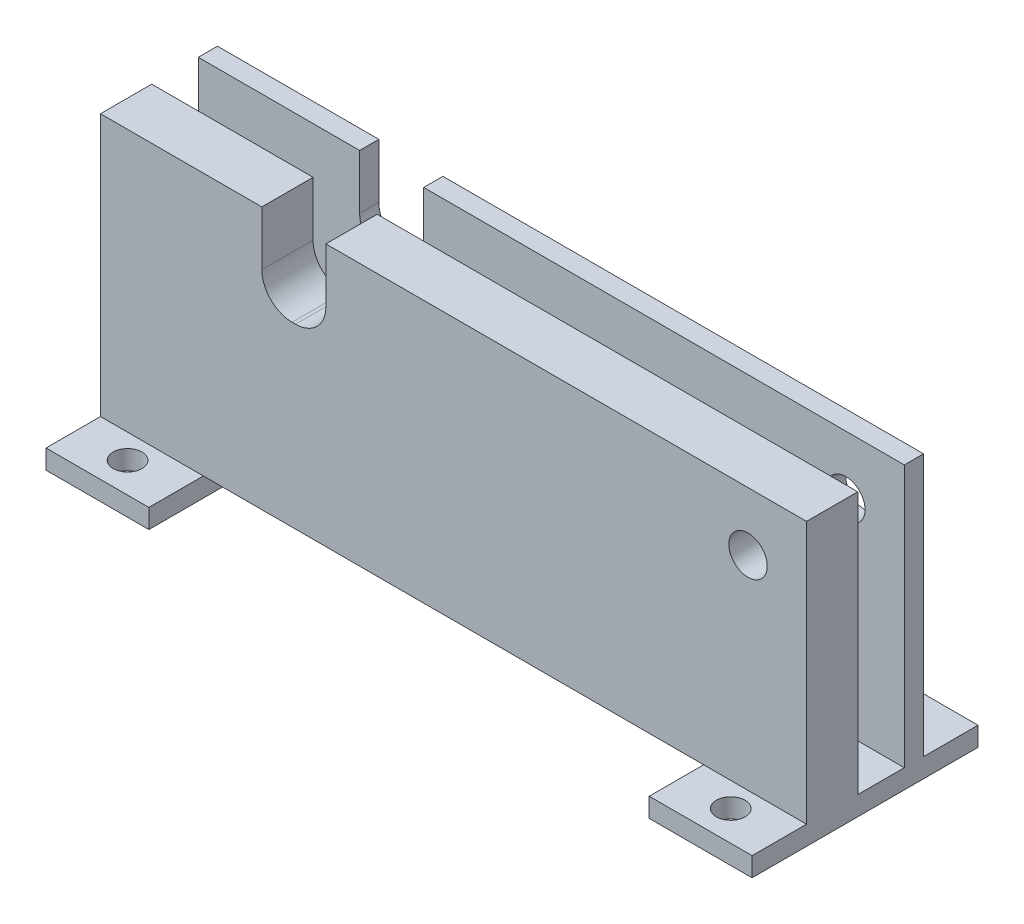
SolidWorks part; units mm, degrees
ref_plane "Alzado" through (0, 0, 0) normal (0, 0, 1) x (1, 0, 0)
ref_plane "Planta" through (0, 0, 0) normal (0, 1, 0) x (1, 0, 0)
ref_plane "Vista lateral" through (0, 0, 0) normal (1, 0, 0) x (0, 0, -1)
sketch "Croquis1" plane through (0, 0, 0) normal (0, 0, 1) x (1, 0, 0)
  line L1 (-175, -65) -> (175, -65)
  line L2 (-175, -65) -> (-175, 65)
  line L3 (-175, 65) -> (175, 65)
  line L4 (175, -65) -> (175, 65)
  line L5 (-175, -65) -> (175, 65) construction
  line L6 (-175, 65) -> (175, -65) construction
  point P0 (0, 0)
  dimension "D1" = 350
  dimension "D2" = 130
extrude "Saliente-Extruir1" add sketch "Croquis1" along normal mid plane 58
sketch "Croquis2" plane through (0, -65, 0) normal (0, -1, 0) x (1, 0, 0)
  line L0 (-175, 29) -> (-175, -29) construction
  line L1 (-124, -56) -> (-175, -56)
  line L2 (-124, -56) -> (-124, 56)
  line L3 (-124, 56) -> (-175, 56)
  line L4 (-175, -56) -> (-175, 56)
  line L5 (-124, -56) -> (-175, 56) construction
  line L6 (-124, 56) -> (-175, -56) construction
  line L7 (192.7092, 0) -> (-269.2261, 0) construction
  line L8 (-149.5, 56) -> (-149.5, -56) construction
  line L9 (-149.5, 48.2) -> (-181.1187, 48.2) construction
  line L10 (0, 85.8102) -> (0, -80.4627) construction
  line L11 (124, 56) -> (175, 56)
  line L12 (175, -56) -> (175, 56)
  line L13 (124, -56) -> (175, -56)
  line L14 (124, -56) -> (124, 56)
  circle A0 centre (-149.5, 41.0562) radius 7.1438
  circle A1 centre (-149.5, -41.0562) radius 7.1438
  circle A2 centre (149.5, -41.0562) radius 7.1438
  circle A3 centre (149.5, 41.0562) radius 7.1438
  point P0 (-149.5, 0)
  dimension "D3" = 14.2875
  dimension "D1" = 51
  dimension "D2" = 112
  dimension "D4" = 7.8
extrude "Saliente-Extruir2" add sketch "Croquis2" along normal blind 9.525
sketch "Croquis3" plane through (0, 0, -29) normal (0, 0, -1) x (-1, 0, 0)
  line L0 (-175, 65) -> (175, 65) construction
  line L1 (95, 65) -> (63.25, 65)
  line L2 (95, 65) -> (95, 38)
  line L3 (80, 23) -> (78.25, 23)
  line L4 (63.25, 65) -> (63.25, 38)
  line L5 (175, 65) -> (175, -65) construction
  arc A0 (95, 38) -> (80, 23) centre (80, 38) cw
  arc A1 (78.25, 23) -> (63.25, 38) centre (78.25, 38) cw
  point P10 (95, 23)
  point P13 (63.25, 23)
  dimension "D4" = 15
  dimension "D1" = 80
  dimension "D2" = 31.75
  dimension "D3" = 42
extrude "Cortar-Extruir1" cut sketch "Croquis3" against normal blind 99.525
sketch "Croquis4" plane through (175, 0, 0) normal (1, 0, 0) x (0, 0, -1)
  line L0 (-29, 65) -> (29, 65) construction
  line L1 (-3.6, -65) -> (19.475, -65)
  line L2 (-3.6, -65) -> (-3.6, 65)
  line L3 (-3.6, 65) -> (19.475, 65)
  line L4 (19.475, -65) -> (19.475, 65)
  line L5 (-29, -65) -> (-29, 65) construction
  line L6 (29, -65) -> (29, 65) construction
  line L7 (-29, -65) -> (-56, -65) construction
  point P8 (18.8822, 65)
  dimension "D1" = 25.4
  dimension "D2" = 9.525
extrude "Cortar-Extruir2" cut sketch "Croquis4" against normal through all
sketch "Croquis5" plane through (0, 0, -29) normal (0, 0, -1) x (-1, 0, 0)
  line L0 (-175, -65) -> (-175, 65) construction
  line L1 (-175, 65) -> (63.25, 65) construction
  circle A0 centre (-146, 36) radius 9.525
  dimension "D2" = 19.05
  dimension "D1" = 29
  dimension "D3" = 29
extrude "Cortar-Extruir3" cut sketch "Croquis5" against normal blind 99.525
